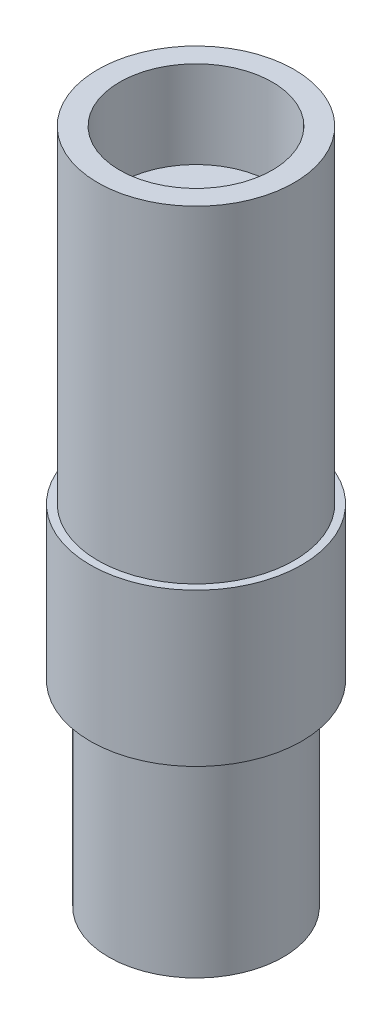
SolidWorks part; units mm, degrees
material "Polyetheretherketone (PEEK)"
ref_plane "Front Plane" through (0, 0, 0) normal (0, 0, 1) x (1, 0, 0)
ref_plane "Top Plane" through (0, 0, 0) normal (0, 1, 0) x (1, 0, 0)
ref_plane "Right Plane" through (0, 0, 0) normal (1, 0, 0) x (0, 0, -1)
sketch "Sketch1" plane through (0, 0, 0) normal (0, 1, 0) x (1, 0, 0)
  circle A0 centre (0, 0) radius 4.5
  dimension "D1" = 9
extrude "Boss-Extrude1" add sketch "Sketch1" along normal blind 15
hole_wizard "Ø6.0mm Dowel Hole1" positions "Sketch4" profile "Sketch3" hole size "Ø6.0" standard "ANSI Metric"
sketch "Sketch4" plane through (0, 15, 0) normal (0, 1, 0) x (1, 0, 0)
  point P0 (0, 0)
sketch "Sketch3" plane through (0, 15, 0) normal (1, 0, 0) x (0, 0, 1)
  line L0 (0, 0) -> (0, 4)
  line L1 (0, 4) -> (3.5, 4)
  line L2 (3.5, 4) -> (3.5, 0)
  line L5 (3.5, 0) -> (0, 0)
  line L10 (0, 4) -> (-3.5, 4) construction
  line L11 (0, -6.35) -> (0, 107.95) construction
  dimension "Hole Dia." = 7
  dimension "Hole Depth" = 4
  dimension "Drill Angle" = 180
sketch "Sketch5" plane through (0, 0, 0) normal (0, 1, 0) x (1, 0, 0)
  circle A0 centre (0, 0) radius 4.85
  dimension "D1" = 9.7
extrude "Boss-Extrude2" add sketch "Sketch5" against normal blind 7
sketch "Sketch6" plane through (0, -7, 0) normal (0, -1, 0) x (1, 0, 0)
  circle A0 centre (0, 0) radius 4
  dimension "D1" = 8
extrude "Boss-Extrude3" add sketch "Sketch6" along normal blind 9
hole_wizard "Ø6.0mm Dowel Hole2" positions "Sketch14" profile "Sketch13" hole size "Ø6.0" standard "ANSI Metric"
sketch "Sketch14" plane through (0, -16, 0) normal (0, -1, 0) x (-1, 0, 0)
  point P0 (0, 0)
sketch "Sketch13" plane through (0, -16, 0) normal (1, 0, 0) x (0, 0, -1)
  line L0 (0, 0) -> (0, 15)
  line L1 (0, 15) -> (3, 15)
  line L2 (3, 15) -> (3, 0)
  line L5 (3, 0) -> (0, 0)
  line L10 (0, 15) -> (-3, 15) construction
  line L11 (0, -6.35) -> (0, 107.95) construction
  dimension "Hole Dia." = 6
  dimension "Hole Depth" = 15
  dimension "Drill Angle" = 180
hole_wizard "Tap Drill for M1.6x0.35 Tap3" positions "Sketch20" profile "Sketch19" hole size "M1.6x0.35" standard "ANSI Metric"
sketch "Sketch20" plane through (0, -1, 0) normal (0, -1, 0) x (-1, 0, 0)
  point P0 (1.75, 0)
  point P2 (-1.75, 0)
sketch "Sketch19" plane through (-1.75, -1, 0) normal (1, 0, 0) x (0, 0, -1)
  line L0 (0, 0) -> (0, 41)
  line L1 (0, 41) -> (0.625, 41)
  line L2 (0.625, 41) -> (0.625, 0)
  line L5 (0.625, 0) -> (0, 0)
  line L10 (0, 41) -> (-0.625, 41) construction
  line L11 (0, -6.35) -> (0, 107.95) construction
  dimension "Hole Dia." = 1.25
  dimension "Hole Depth" = 41
  dimension "Drill Angle" = 180
